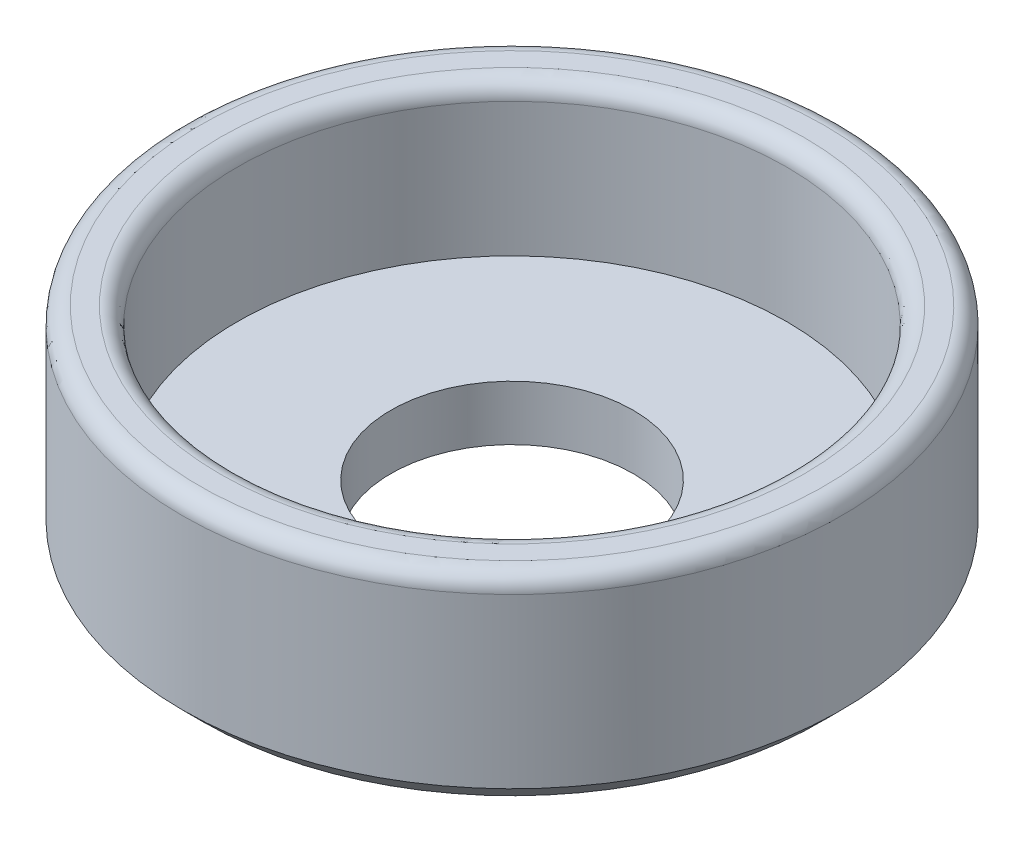
SolidWorks part; units mm, degrees
ref_plane "Front Plane" through (0, 0, 0) normal (0, 0, 1) x (1, 0, 0)
ref_plane "Top Plane" through (0, 0, 0) normal (0, 1, 0) x (1, 0, 0)
ref_plane "Right Plane" through (0, 0, 0) normal (1, 0, 0) x (0, 0, -1)
sketch "Sketch1" plane through (0, 0, 0) normal (0, 0, 1) x (1, 0, 0)
  line L0 (0, 0) -> (4.8, 0)
  line L1 (4.8, 0) -> (4.8, 3)
  line L2 (4.8, 3) -> (4, 3)
  line L3 (4, 3) -> (4, 0.8)
  line L4 (4, 0.8) -> (0, 0.8)
  line L5 (0, 0.8) -> (0, 0)
  dimension "D1" = 0.8
  dimension "D2" = 4
  dimension "D3" = 3
revolve "Revolve1" add sketch "Sketch1" angle 360 about L5
sketch "Sketch2" plane through (0, 0.8, 0) normal (0, 1, 0) x (1, 0, 0)
  circle A0 centre (0, 0) radius 1.765
  dimension "D1" = 3.53
extrude "Cut-Extrude1" cut sketch "Sketch2" against normal through all
fillet "Fillet1" radius 0.25 2 edges at (0, 3, 4) (0, 3, 4.8)
chamfer "Chamfer1" distance 0.3 angle 45 1 edges at (0, 0, 4.8)
